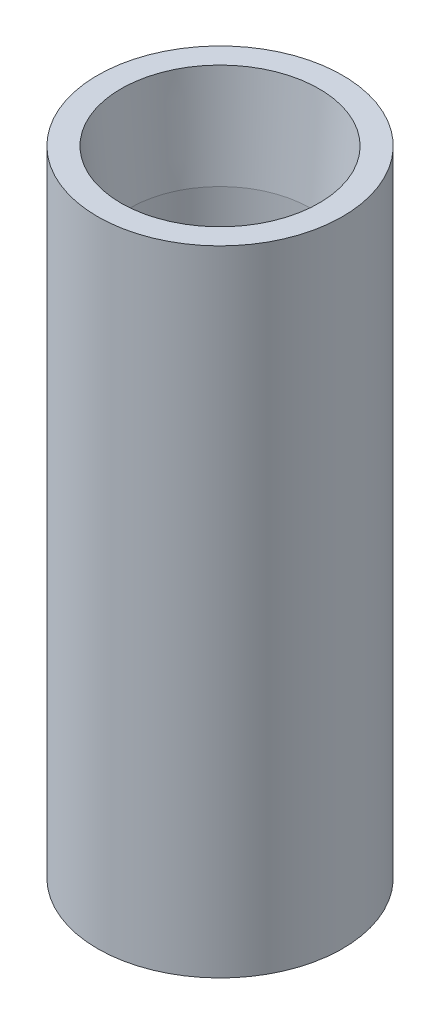
SolidWorks part; units mm, degrees
ref_plane "Front Plane" through (0, 0, 0) normal (0, 0, 1) x (1, 0, 0)
ref_plane "Top Plane" through (0, 0, 0) normal (0, 1, 0) x (1, 0, 0)
ref_plane "Right Plane" through (0, 0, 0) normal (1, 0, 0) x (0, 0, -1)
sketch "Sketch1" plane through (0, 0, 0) normal (0, 1, 0) x (1, 0, 0)
  circle A0 centre (0, 0) radius 12.7
  dimension "D1" = 25.4
extrude "Boss-Extrude1" add sketch "Sketch1" against normal blind 12.7 draft 5
sketch "Sketch2" plane through (0, 0, 0) normal (0, 1, 0) x (1, 0, 0)
  circle A0 centre (0, 0) radius 3.175
  dimension "D1" = 6.35
extrude "Cut-Extrude1" cut sketch "Sketch2" against normal through all
sketch "Sketch3" plane through (0, 0, 0) normal (0, 0, 1) x (1, 0, 0)
  line L0 (0, -13.4041) -> (0, 0) construction
sketch "Sketch7" plane through (0, -12.7, 0) normal (0, -1, 0) x (1, 0, 0)
  line L0 (0, 0) -> (-8.636, 0) construction
  line L1 (0, 0) -> (4.318, 7.479) construction
  circle A0 centre (-8.636, 0) radius 1.27
  circle A2 centre (4.318, 7.479) radius 1.27
  dimension "D1" = 2.54
  dimension "D2" = 8.636
  dimension "D4" = 120
  dimension "D3" = 2
extrude "Cut-Extrude2" cut sketch "Sketch7" against normal blind 7.62 contours A2 | A0
sketch "Sketch10" plane through (0, 0, 0) normal (0, 1, 0) x (1, 0, 0)
  circle A1 centre (0, 0) radius 15.7
  dimension "D2" = 31.4
extrude "Boss-Extrude2" add sketch "Sketch10" against normal blind 81.28
sketch "Sketch11" plane through (0, 0, 0) normal (0, 1, 0) x (1, 0, 0)
  circle A0 centre (0, 0) radius 12.7
  dimension "D1" = 25.4
extrude "Cut-Extrude3" cut sketch "Sketch11" against normal blind 12.7 draft 5
sketch "Sketch12" plane through (0, -12.7, 0) normal (0, 1, 0) x (1, 0, 0)
  circle A0 centre (0, 0) radius 11.5889
extrude "Cut-Extrude4" cut sketch "Sketch12" against normal blind 63.5
equation "\"D1@Sketch7\" = \"D1@Sketch1\" / 10"
equation "\"D2@Sketch7\" = ( \"D1@Sketch1\" / 2 ) - ( \"D1@Sketch7\" * 1.6 )"
equation "\"D2@Sketch10\" = \"D1@Sketch1\" + 6"
equation "\"D1@Sketch11\" = \"D1@Sketch1\""
